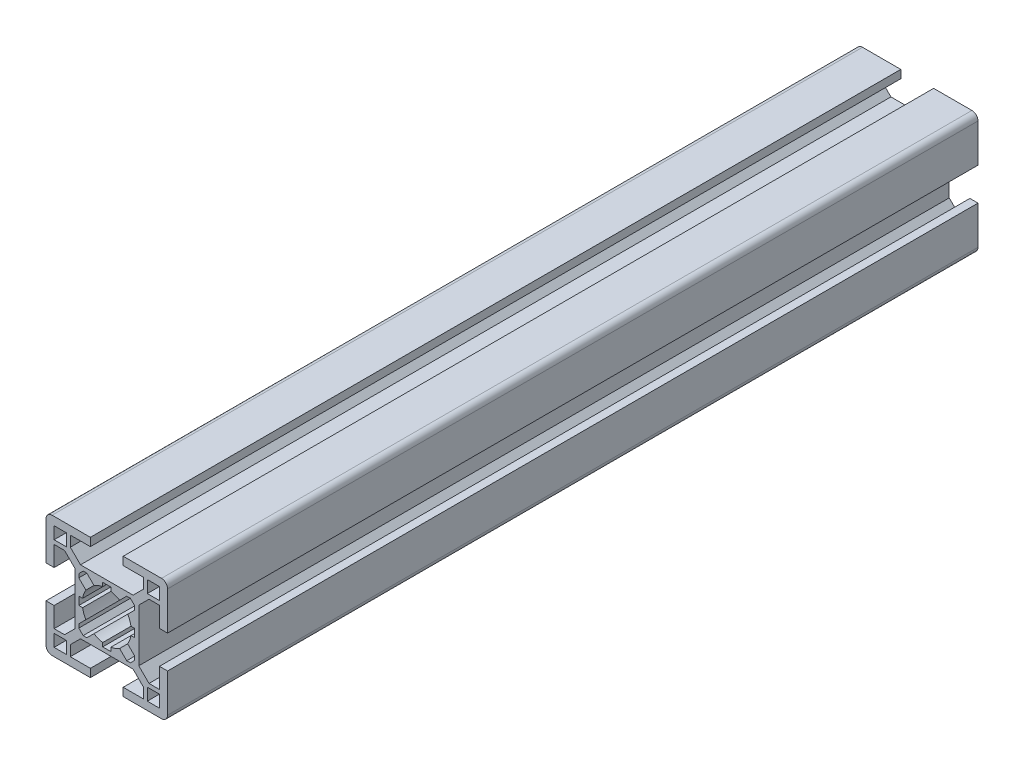
SolidWorks part; units mm, degrees
material "6063-T5"
ref_plane "Plano frontal" through (0, 0, 0) normal (0, 0, 1) x (1, 0, 0)
ref_plane "Plano superior" through (0, 0, 0) normal (0, 1, 0) x (1, 0, 0)
ref_plane "Plano direito" through (0, 0, 0) normal (1, 0, 0) x (0, 0, -1)
sketch "Esboço1" plane through (0, 0, 0) normal (0, 0, 1) x (1, 0, 0)
  line L0 (15, 13.5) -> (15, 4.05)
  line L1 (-13.5, 15) -> (-4.05, 15)
  line L8 (-9, 13) -> (-9, 10.4142)
  line L9 (-10, 13) -> (-10, 10)
  line L10 (-9, 13) -> (-4.05, 13)
  line L11 (-6.9, 1) -> (-6.9, 0)
  line L12 (-13, 13) -> (-10, 13)
  line L13 (-10.4142, 9) -> (-7.9, 6.4858)
  line L14 (-6.9, 1) -> (-5.9668, 1)
  line L15 (-15, 4.05) -> (-13, 4.05)
  line L16 (-6.4858, 7.9) -> (0, 7.9)
  line L17 (-4.9126, 6.9) -> (-3.1673, 5.1547)
  line L18 (-5.8279, 6.9) -> (-4.9126, 6.9)
  line L19 (-6.9, 5.8279) -> (-6.9, 4.9126)
  line L20 (-4.05, 15) -> (-4.05, 13)
  line L21 (13, 9) -> (10.4142, 9)
  line L22 (-1, 6.9) -> (-1, 5.9668)
  line L23 (-6.9, 4.9126) -> (-5.1547, 3.1673)
  line L24 (-5.8279, 6.9) -> (-6.9, 5.8279)
  line L25 (-7.9, 6.4858) -> (-7.9, 0)
  line L26 (13, 10) -> (10, 10)
  line L27 (-9, 10.4142) -> (-6.4858, 7.9)
  line L28 (13, 9) -> (13, 4.05)
  line L29 (-1, 6.9) -> (0, 6.9)
  line L30 (-6.4858, 6.9) -> (0, 6.9) construction
  line L31 (-13, 13) -> (-13, 10)
  line L32 (-13, 9) -> (-13, 4.05)
  line L33 (-15, 15) -> (-15, -15) construction
  line L34 (-15, 15) -> (15, 15) construction
  line L35 (-13, 10) -> (-10, 10)
  line L36 (-13, 9) -> (-10.4142, 9)
  line L37 (-13, 13) -> (13, 13) construction
  line L38 (-15, 13.5) -> (-15, 4.05)
  line L39 (1, 6.9) -> (0, 6.9)
  line L40 (13, 13) -> (13, 10)
  line L41 (-13, 13) -> (-13, -13) construction
  line L42 (9, 10.4142) -> (6.4858, 7.9)
  line L43 (1, 6.9) -> (1, 5.9668)
  line L44 (4.05, 15) -> (4.05, 13)
  line L45 (7.9, 6.4858) -> (7.9, 0)
  line L46 (6.9, 4.9126) -> (5.1547, 3.1673)
  line L47 (6.9, 5.8279) -> (6.9, 4.9126)
  line L48 (5.8279, 6.9) -> (4.9126, 6.9)
  line L49 (-7.9, 7.9) -> (7.9, 7.9) construction
  line L50 (15, 4.05) -> (13, 4.05)
  line L51 (6.9, 1) -> (5.9668, 1)
  line L52 (4.9126, 6.9) -> (3.1673, 5.1547)
  line L53 (6.9, 5.8279) -> (5.8279, 6.9)
  line L54 (6.4858, 7.9) -> (0, 7.9)
  line L55 (10.4142, 9) -> (7.9, 6.4858)
  line L56 (6.9, 1) -> (6.9, 0)
  line L57 (13, 13) -> (10, 13)
  line L58 (9, 13) -> (4.05, 13)
  line L59 (10, 13) -> (10, 10)
  line L60 (9, 13) -> (9, 10.4142)
  line L61 (13.5, 15) -> (4.05, 15)
  line L62 (13.5, -15) -> (4.05, -15)
  line L63 (9, -13) -> (9, -10.4142)
  line L64 (10, -13) -> (10, -10)
  line L65 (9, -13) -> (4.05, -13)
  line L66 (-7.9, 7.9) -> (-7.9, -7.9) construction
  line L67 (6.9, -1) -> (6.9, 0)
  line L68 (-15, -15) -> (15, -15) construction
  line L69 (15, 15) -> (15, -15) construction
  line L70 (13, 13) -> (13, -13) construction
  line L71 (-13, -13) -> (13, -13) construction
  line L72 (7.9, 7.9) -> (7.9, -7.9) construction
  line L73 (-7.9, -7.9) -> (7.9, -7.9) construction
  line L74 (13, -13) -> (10, -13)
  line L75 (10.4142, -9) -> (7.9, -6.4858)
  line L76 (6.9, -1) -> (5.9668, -1)
  line L77 (15, -4.05) -> (13, -4.05)
  line L78 (6.4858, -7.9) -> (0, -7.9)
  line L79 (4.9126, -6.9) -> (3.1673, -5.1547)
  line L80 (5.8279, -6.9) -> (4.9126, -6.9)
  line L81 (6.9, -5.8279) -> (6.9, -4.9126)
  line L82 (4.05, -15) -> (4.05, -13)
  line L83 (1, -6.9) -> (1, -5.9668)
  line L84 (6.9, -4.9126) -> (5.1547, -3.1673)
  line L85 (5.8279, -6.9) -> (6.9, -5.8279)
  line L86 (7.9, -6.4858) -> (7.9, 0)
  line L87 (9, -10.4142) -> (6.4858, -7.9)
  line L88 (1, -6.9) -> (0, -6.9)
  line L89 (13, -13) -> (13, -10)
  line L90 (13, -9) -> (13, -4.05)
  line L91 (13, -10) -> (10, -10)
  line L92 (13, -9) -> (10.4142, -9)
  line L93 (15, -13.5) -> (15, -4.05)
  line L94 (-15, -13.5) -> (-15, -4.05)
  line L95 (-13, -9) -> (-10.4142, -9)
  line L96 (-13, -10) -> (-10, -10)
  line L97 (-13, -9) -> (-13, -4.05)
  line L98 (-1, -6.9) -> (0, -6.9)
  line L99 (-13, -13) -> (-13, -10)
  line L100 (-9, -10.4142) -> (-6.4858, -7.9)
  line L101 (-1, -6.9) -> (-1, -5.9668)
  line L102 (-4.05, -15) -> (-4.05, -13)
  line L103 (-7.9, -6.4858) -> (-7.9, 0)
  line L104 (-6.9, -4.9126) -> (-5.1547, -3.1673)
  line L105 (-6.9, -5.8279) -> (-6.9, -4.9126)
  line L106 (-5.8279, -6.9) -> (-4.9126, -6.9)
  line L107 (-15, -4.05) -> (-13, -4.05)
  line L108 (-6.9, -1) -> (-5.9668, -1)
  line L109 (-4.9126, -6.9) -> (-3.1673, -5.1547)
  line L110 (-6.9, -5.8279) -> (-5.8279, -6.9)
  line L111 (-6.4858, -7.9) -> (0, -7.9)
  line L112 (-10.4142, -9) -> (-7.9, -6.4858)
  line L113 (-6.9, -1) -> (-6.9, 0)
  line L114 (-13, -13) -> (-10, -13)
  line L115 (-9, -13) -> (-4.05, -13)
  line L116 (-10, -13) -> (-10, -10)
  line L117 (-9, -13) -> (-9, -10.4142)
  line L118 (-13.5, -15) -> (-4.05, -15)
  arc A0 (-1, 5.9668) -> (-3.1673, 5.1547) centre (0, 0) ccw
  arc A1 (-5.9668, 1) -> (-5.1547, 3.1673) centre (0, 0) cw
  arc A2 (-13.5, 15) -> (-15, 13.5) centre (-13.5, 13.5) ccw
  arc A3 (5.9668, 1) -> (5.1547, 3.1673) centre (0, 0) ccw
  arc A4 (1, 5.9668) -> (3.1673, 5.1547) centre (0, 0) cw
  arc A5 (15, 13.5) -> (13.5, 15) centre (13.5, 13.5) ccw
  arc A6 (1, -5.9668) -> (3.1673, -5.1547) centre (0, 0) ccw
  arc A7 (5.9668, -1) -> (5.1547, -3.1673) centre (0, 0) cw
  arc A8 (13.5, -15) -> (15, -13.5) centre (13.5, -13.5) ccw
  arc A9 (-5.9668, -1) -> (-5.1547, -3.1673) centre (0, 0) ccw
  arc A10 (-1, -5.9668) -> (-3.1673, -5.1547) centre (0, 0) cw
  arc A11 (-15, -13.5) -> (-13.5, -15) centre (-13.5, -13.5) ccw
  point P139 (0, 0)
  dimension "D1" = 4
extrude "Ressalto-extrusão1" add sketch "Esboço1" along normal mid plane 200
